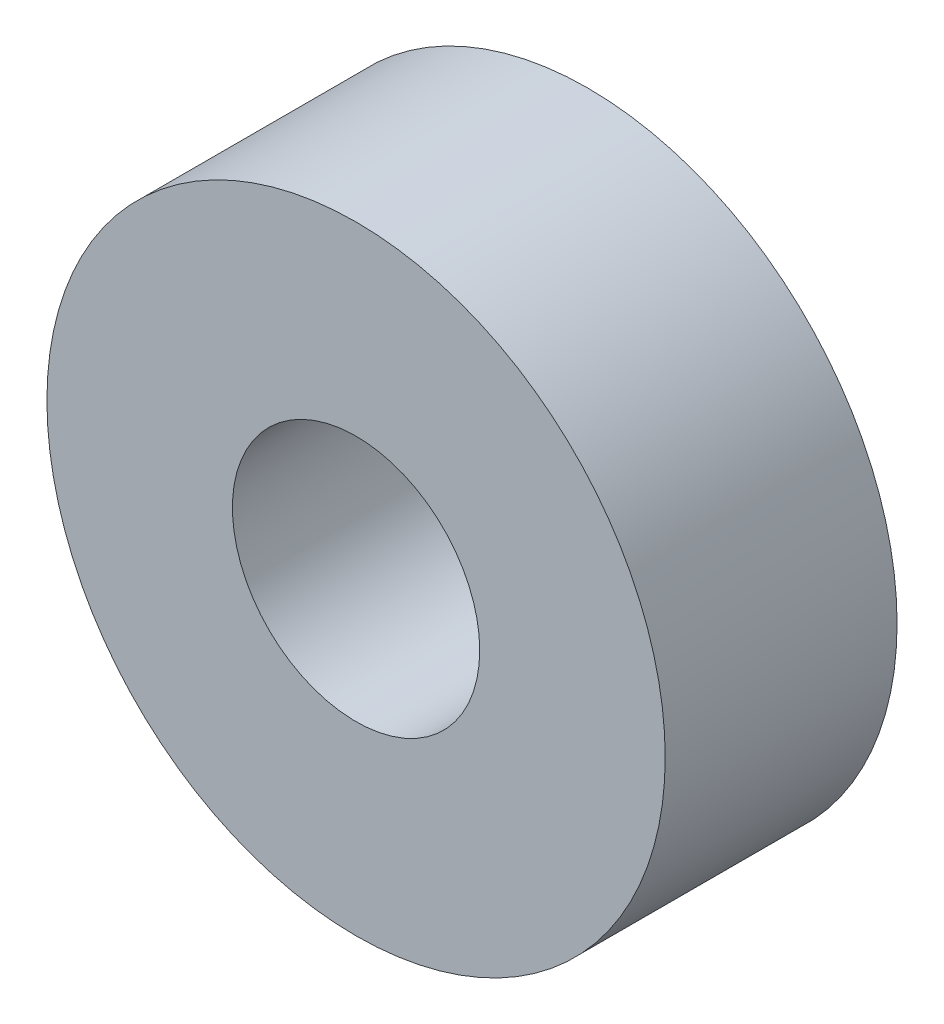
SolidWorks part; units mm, degrees
ref_plane "Front Plane" through (0, 0, 0) normal (0, 0, 1) x (1, 0, 0)
ref_plane "Top Plane" through (0, 0, 0) normal (0, 1, 0) x (1, 0, 0)
ref_plane "Right Plane" through (0, 0, 0) normal (1, 0, 0) x (0, 0, -1)
sketch "Sketch1" plane through (0, 0, 0) normal (0, 0, 1) x (1, 0, 0)
  line L0 (0, 1.6) -> (0, 4) construction
  line L1 (0, -1.6) -> (0, -4) construction
  circle A0 centre (0, 0) radius 4
  circle A1 centre (0, 0) radius 1.6
  dimension "OD" = 8
  dimension "ID" = 3.2
sketch "Sketch2" plane through (0, 0, 0) normal (1, 0, 0) x (0, 0, -1)
  line L0 (-1.5, 1.6) -> (1.5, 1.6) construction
  line L1 (-1.5, -1.6) -> (1.5, -1.6) construction
  line L2 (-1.5, -4) -> (1.5, -4) construction
  line L3 (-1.5, 4) -> (1.5, 4) construction
  dimension "Length" = 3
extrude "Extrude1" add sketch "Sketch1" along normal up to vertex (1.5 mm away) and the other way up to vertex (1.5 mm away) up to point (0, 1.6, 1.5) other way up to point (0, 1.6, -1.5)
sketch "Sketch3" plane through (0, 0, 1.5) normal (0, 0, 1) x (1, 0, 0)
  circle A0 centre (0, 0) radius 1.6 construction
  circle A3 centre (0, 0) radius 1.6
  point P3 (-1.6, 0)
